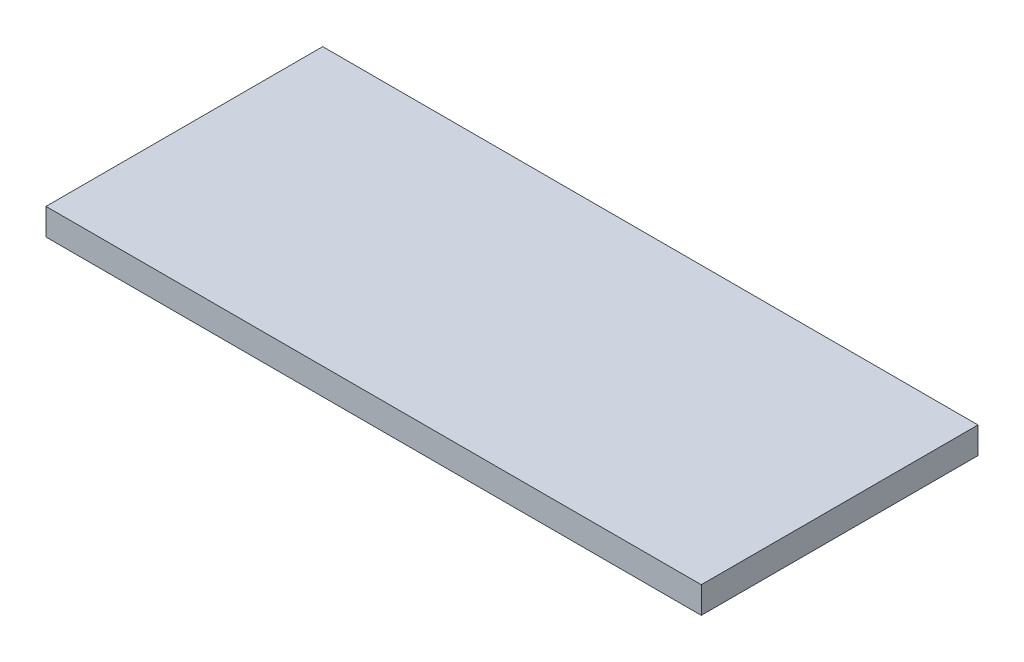
SolidWorks part; units mm, degrees
material "Plain Carbon Steel"
ref_plane "Front Plane" through (0, 0, 0) normal (0, 0, 1) x (1, 0, 0)
ref_plane "Top Plane" through (0, 0, 0) normal (0, 1, 0) x (1, 0, 0)
ref_plane "Right Plane" through (0, 0, 0) normal (1, 0, 0) x (0, 0, -1)
sketch "Sketch1" plane through (0, 0, 0) normal (0, 1, 0) x (1, 0, 0)
  line L0 (0, -55) -> (0, 55) construction
  line L1 (-74, 62.5) -> (74, 62.5)
  line L2 (-74, 62.5) -> (-74, 0)
  line L3 (-74, 0) -> (74, 0)
  line L4 (74, 62.5) -> (74, 0)
  line L5 (-74, 62.5) -> (74, 0) construction
  line L6 (-74, 0) -> (74, 62.5) construction
  line L7 (-55, 0) -> (55, 0) construction
  point P0 (0, 31.25)
  dimension "D1" = 148
  dimension "D2" = 62.5
extrude "Boss-Extrude1" add sketch "Sketch1" along normal blind 6
sketch "Sketch2" plane through (0, 0, 0) normal (0, 1, 0) x (1, 0, 0)
  line L0 (0, -55) -> (0, 55) construction
  line L1 (74, 62.5) -> (-74, 62.5) construction
  circle A0 centre (20, 52.5) radius 3.3
  circle A1 centre (-20, 52.5) radius 3.3
  dimension "D1" = 20
  dimension "D2" = 6.6
  dimension "D3" = 10
extrude "Cut-Extrude1" [suppressed] cut sketch "Sketch2" along normal through all
